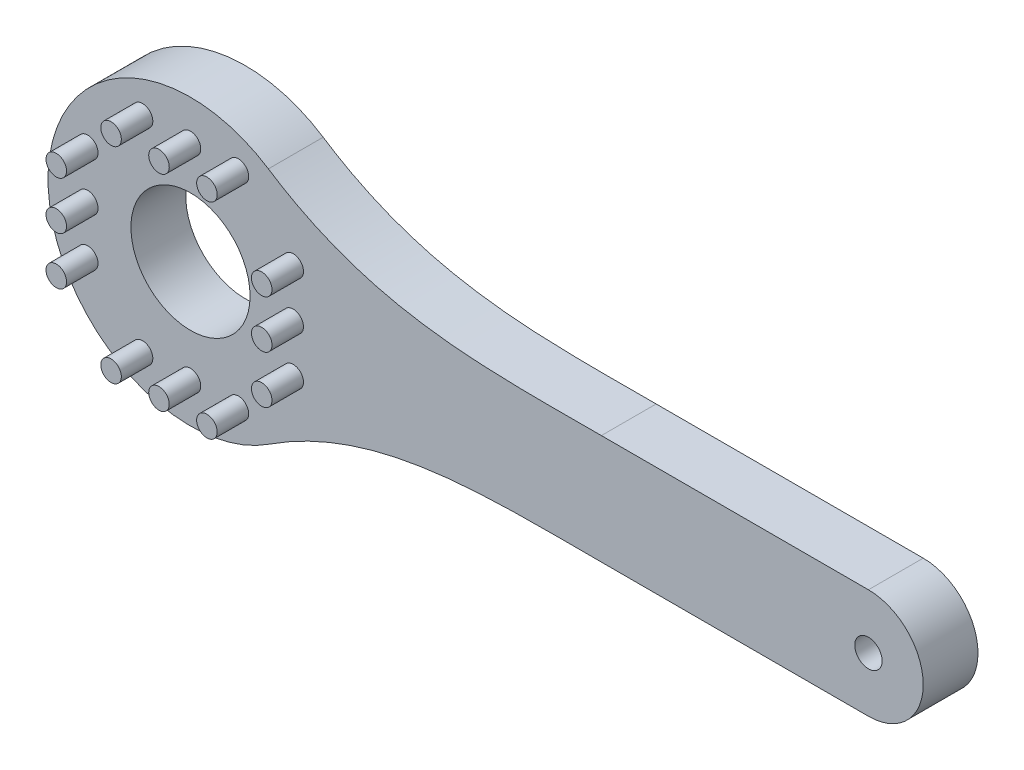
SolidWorks part; units mm, degrees
ref_plane "Front Plane" through (0, 0, 0) normal (0, 0, 1) x (1, 0, 0)
ref_plane "Top Plane" through (0, 0, 0) normal (0, 1, 0) x (1, 0, 0)
ref_plane "Right Plane" through (0, 0, 0) normal (1, 0, 0) x (0, 0, -1)
sketch "Sketch1" plane through (0, 0, 0) normal (0, 0, 1) x (1, 0, 0)
  line L0 (0, 0) -> (52.669, 0) construction
  line L1 (30, 4) -> (49.5, 4)
  line L2 (30, -4) -> (49.5, -4)
  arc A0 (5.6862, 8.7079) -> (5.6862, -8.7079) centre (0, 0) ccw
  circle A1 centre (0, 0) radius 4.35
  arc A2 (49.5, 4) -> (49.5, -4) centre (49.5, 0) cw
  circle A3 centre (49.5, 0) radius 1
  spline S0 degree 3 poles (5.6862, 8.7079) (13.4104, 3.664) (21.2669, 4) (30, 4) knots 0 0 0 0 1 1 1 1
  spline S1 degree 3 poles (5.6862, -8.7079) (13.4104, -3.664) (21.2669, -4) (30, -4) knots 0 0 0 0 1 1 1 1
  dimension "D1" = 20.8
  dimension "D2" = 8.7
  dimension "D8" = 49.5
  dimension "D7" = 2
  dimension "D3" = 4
  dimension "D4" = 4.5
  dimension "D5" = 17.1959
  dimension "D6" = 30
extrude "Boss-Extrude1" add sketch "Sketch1" along normal blind 4
sketch "Sketch2" plane through (0, 0, 4) normal (0, 0, 1) x (1, 0, 0)
  line L0 (0, -55) -> (0, 55) construction
  line L1 (55, 0) -> (-55, 0) construction
  circle A0 centre (0, 0) radius 10.4 construction
  circle A1 centre (0, 0) radius 4.35 construction
  circle A2 centre (0, 7.5) radius 0.75
  circle A3 centre (3.5, 7.5) radius 0.75
  circle A4 centre (-3.5, 7.5) radius 0.75
  circle A5 centre (3.5, -7.5) radius 0.75
  circle A6 centre (0, -7.5) radius 0.75
  circle A7 centre (-3.5, -7.5) radius 0.75
  circle A8 centre (7.5, 0) radius 0.75
  circle A9 centre (7.5, 3.5) radius 0.75
  circle A10 centre (7.5, -3.5) radius 0.75
  circle A11 centre (-7.5, -3.5) radius 0.75
  circle A12 centre (-7.5, 0) radius 0.75
  circle A13 centre (-7.5, 3.5) radius 0.75
  dimension "D1" = 20.8
  dimension "D2" = 8.7
  dimension "D3" = 1.5
  dimension "D5" = 1.5
  dimension "D9" = 1.5
  dimension "D12" = 1.5
  dimension "D4" = 7.5
  dimension "D6" = 3.5
  dimension "D7" = 0
  dimension "D8" = 0
  dimension "D10" = 7.5
  dimension "D11" = 0
  dimension "D13" = 3.5
  dimension "D14" = 0
extrude "Boss-Extrude2" add sketch "Sketch2" along normal blind 2.3
